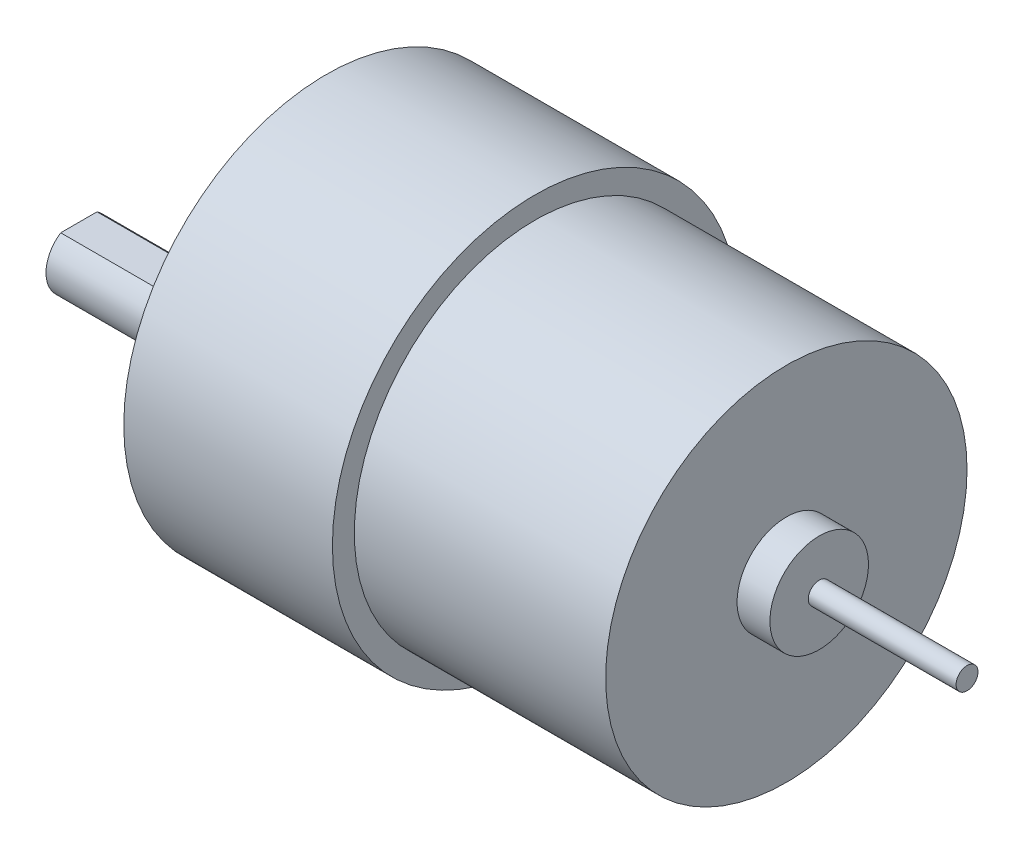
SolidWorks part; units mm, degrees
ref_plane "Front Plane" through (0, 0, 0) normal (0, 0, 1) x (1, 0, 0)
ref_plane "Top Plane" through (0, 0, 0) normal (0, 1, 0) x (1, 0, 0)
ref_plane "Right Plane" through (0, 0, 0) normal (1, 0, 0) x (0, 0, -1)
sketch "Sketch1" plane through (0, 0, 0) normal (1, 0, 0) x (0, 0, -1)
  circle A0 centre (0, 0) radius 18.5
  dimension "D1" = 37
extrude "Boss-Extrude1" add sketch "Sketch1" along normal blind 19.05
sketch "Sketch2" plane through (19.05, 0, 0) normal (1, 0, 0) x (0, 0, -1)
  circle A0 centre (0, 0) radius 16.5
  dimension "D1" = 33
extrude "Boss-Extrude2" add sketch "Sketch2" along normal blind 22.95
sketch "Sketch3" plane through (42, 0, 0) normal (1, 0, 0) x (0, 0, -1)
  circle A0 centre (0, 0) radius 4.5
  dimension "D1" = 9
extrude "Boss-Extrude3" add sketch "Sketch3" along normal blind 3
sketch "Sketch4" plane through (45, 0, 0) normal (1, 0, 0) x (0, 0, -1)
  circle A0 centre (0, 0) radius 1
  dimension "D1" = 2
extrude "Boss-Extrude4" add sketch "Sketch4" along normal blind 13.5
sketch "Sketch5" plane through (0, 0, 0) normal (-1, 0, 0) x (0, 0, 1)
  circle A0 centre (0, -7) radius 6
  point P2 (0, 0)
  dimension "D1" = 7
  dimension "D2" = 12
extrude "Boss-Extrude5" add sketch "Sketch5" along normal blind 4.6
sketch "Sketch7" plane through (-4.6, 0, 0) normal (-1, 0, 0) x (0, 0, 1)
  circle A0 centre (0, -7) radius 3
  dimension "D1" = 6
extrude "Boss-Extrude6" add sketch "Sketch7" along normal blind 6
sketch "Sketch8" plane through (-10.6, 0, 0) normal (-1, 0, 0) x (0, 0, 1)
  line L0 (-1.6583, -4.5) -> (1.6583, -4.5)
  line L1 (-3.5519, -10) -> (4.8094, -10) construction
  circle A0 centre (0, -7) radius 3 construction
  arc A1 (-1.6583, -4.5) -> (1.6583, -4.5) centre (0, -7) ccw
  dimension "D1" = 5.5
extrude "Boss-Extrude7" add sketch "Sketch8" along normal blind 12
